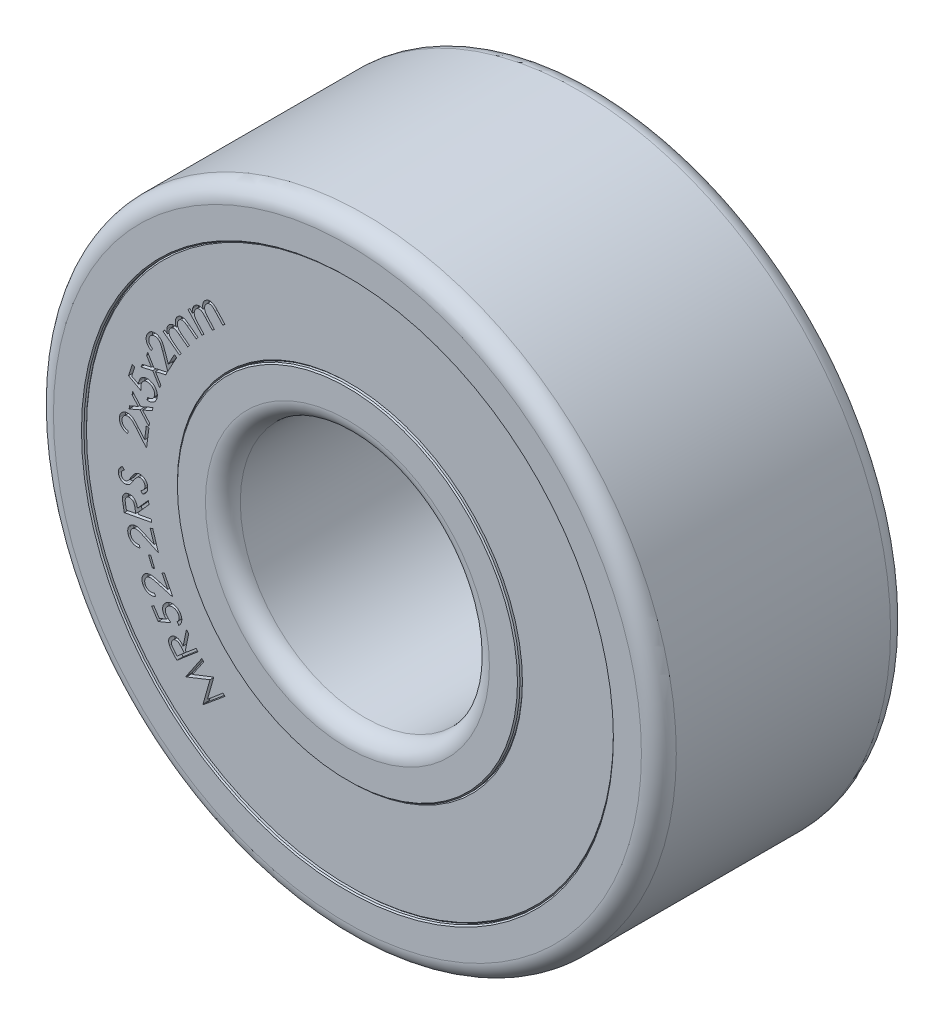
SolidWorks part; units mm, degrees
material "AISI 316 Annealed Stainless Steel Bar (SS)"
ref_plane "Front" through (0, 0, 0) normal (0, 0, 1) x (1, 0, 0)
ref_plane "Top" through (0, 0, 0) normal (0, 1, 0) x (1, 0, 0)
ref_plane "Right" through (0, 0, 0) normal (1, 0, 0) x (0, 0, -1)
sketch "LAYOUT R" plane through (0, 0, 0) normal (1, 0, 0) x (0, 0, -1)
  line L0 (-1, 1) -> (1, 1)
  line L1 (1, -2.5) -> (-1, -2.5) construction
  line L2 (1, -2.5) -> (1, 2.5) construction
  line L3 (1, 2.5) -> (-1, 2.5)
  line L4 (-1, -2.5) -> (-1, 2.5) construction
  line L5 (1, -2.5) -> (-1, 2.5) construction
  line L6 (1, 2.5) -> (-1, -2.5) construction
  line L7 (-1, 1.375) -> (1, 1.375)
  line L8 (-1, 2.125) -> (1, 2.125)
  line L11 (-17.5, 0) -> (17.5, 0) construction
  line L12 (-1, 2.5) -> (-1, 2.125)
  line L13 (1, 2.5) -> (1, 2.125)
  line L14 (-1, 2.125) -> (-1, 1.375)
  line L15 (1, 2.125) -> (1, 1.375)
  line L16 (-1, 1.375) -> (-1, 1)
  line L17 (1, 1.375) -> (1, 1)
  line L18 (-0.98, 2.125) -> (-0.98, 1.375)
  line L19 (0.98, 2.125) -> (0.98, 1.375)
  point P0 (0, 0)
  point P15 (0, 0)
  dimension "D1" = 2
  dimension "D2" = 5
  dimension "D3" = 1
  dimension "D6" = 0.02
  dimension "D7" = 0.02
  dimension "D4" = 1.375
  dimension "D5" = 2.125
sketch "Sketch R, INNER BODY" plane through (0, 0, 0) normal (1, 0, 0) x (0, 0, -1)
  line L0 (-1, 1) -> (1, 1) construction
  line L2 (-1, 1.375) -> (1, 1.375) construction
  line L4 (-1, 1) -> (1, 1)
  line L6 (-1, 1.375) -> (1, 1.375)
  line L8 (1, 1.375) -> (1, 1) construction
  line L9 (-1, 1.375) -> (-1, 1) construction
  line L10 (1, 1.375) -> (1, 1)
  line L11 (-1, 1.375) -> (-1, 1)
  line L12 (-17.5, 0) -> (17.5, 0) construction
  line L13 (-17.5, 0) -> (17.5, 0) construction
sketch "Sketch R, OUTER BODY" plane through (0, 0, 0) normal (1, 0, 0) x (0, 0, -1)
  line L2 (-1, 2.125) -> (1, 2.125) construction
  line L3 (1, 2.5) -> (-1, 2.5) construction
  line L6 (-1, 2.125) -> (1, 2.125)
  line L7 (1, 2.5) -> (-1, 2.5)
  line L8 (-17.5, 0) -> (17.5, 0) construction
  line L9 (-17.5, 0) -> (17.5, 0) construction
  line L10 (1, 2.5) -> (1, 2.125) construction
  line L11 (-1, 2.5) -> (-1, 2.125) construction
  line L12 (1, 2.5) -> (1, 2.125)
  line L13 (-1, 2.5) -> (-1, 2.125)
sketch "Sketch R, SEAL FACES" plane through (0, 0, 0) normal (1, 0, 0) x (0, 0, -1)
  line L0 (-17.5, 0) -> (17.5, 0) construction
  line L1 (-17.5, 0) -> (17.5, 0) construction
  line L3 (-1, 1.375) -> (1, 1.375) construction
  line L5 (-1, 2.125) -> (1, 2.125) construction
  line L7 (-0.98, 1.375) -> (0.98, 1.375)
  line L9 (-0.98, 2.125) -> (0.98, 2.125)
  line L10 (0.98, 2.125) -> (0.98, 1.375) construction
  line L11 (-0.98, 2.125) -> (-0.98, 1.375) construction
  line L12 (0.98, 2.125) -> (0.98, 1.375)
  line L13 (-0.98, 2.125) -> (-0.98, 1.375)
revolve "Revolve INNER BODY" add sketch "Sketch R, INNER BODY" angle 360 about L13
fillet "Fillet INNER BODY" radius 0.14 2 edges at (1, 0, 1) (1, 0, -1)
chamfer "Chamfer INNER BODY" distance 0.01 angle 45 2 edges at (1.375, 0, -1) (1.375, 0, 1)
revolve "Revolve OUTER BODY" add sketch "Sketch R, OUTER BODY" angle 360 about L9
fillet "Fillet OUTER BODY" radius 0.14 2 edges at (2.5, 0, -1) (2.5, 0, 1)
chamfer "Chamfer OUTER BODY" distance 0.01 angle 45 2 edges at (2.125, 0, 1) (2.125, 0, -1)
revolve "Revolve SEALS" add sketch "Sketch R, SEAL FACES" angle 360 about L1
chamfer "Chamfer SEALS" distance 0.01 angle 45 4 edges at (1.375, 0, -0.98) (2.125, 0, -0.98) (2.125, 0, 0.98) (1.375, 0, 0.98)
sketch "Sketch TEXT RADIUS 1 — MANUALLY ASSIGN TEXT AND FONT SIZE (FROM EQUATIONS)" plane through (0, 0, 0.98) normal (0, 0, 1) x (1, 0, 0)
  circle A0 centre (0, 0) radius 1.6375 construction
  text T0 "MR52-2RS  2x5x2mm" font "Century Gothic" height 0.225
  dimension "D1" = 3.275
extrude "Cut-Extrude SEAL LABEL 1" cut sketch "Sketch TEXT RADIUS 1 — MANUALLY ASSIGN TEXT AND FONT SIZE (FROM EQUATIONS)" against normal blind 0.05
sketch "Sketch TEXT RADIUS 2 — MANUALLY ASSIGN TEXT AND FONT SIZE (FROM EQUATIONS)" plane through (0, 0, -0.98) normal (0, 0, -1) x (-1, 0, 0)
  circle A0 centre (0, 0) radius 1.6375 construction
  text T0 "MR52-2RS  2x5x2mm" font "Century Gothic" height 0.225
  dimension "D1" = 3.275
extrude "Cut-Extrude SEAL LABEL 2" cut sketch "Sketch TEXT RADIUS 2 — MANUALLY ASSIGN TEXT AND FONT SIZE (FROM EQUATIONS)" against normal blind 0.05
equation "\"_i__BORE\"= 2"
equation "\"_i__OUTSIDE_DIAMETER\"= 5"
equation "\"_i__WIDTH\"= 2"
equation "\"_i_optional__TEXT_RADIUS_ADJUSTMENT\"= 0"
equation "\"_output__FONT_SIZE_mm\"= \"BODY_SPAN__SEAL__OF_RADIUS\" * \"param__FONT_SIZE_RATIO\"'MANUALLY ASSIGN TO FONT"
equation "\"BODY__HALF_WIDTH\"= \"_i__WIDTH\" / 2"
equation "\"BODY_SPAN___OF_DIAMETER\"= \"_i__OUTSIDE_DIAMETER\" - \"_i__BORE\""
equation "\"BODY_SPAN___OF_RADIUS\"= \"BODY_SPAN___OF_DIAMETER\" / 2"
equation "\"BODY_SPAN__BORE_AND_OD__OF RADIUS\"= ( \"BODY_SPAN___OF_RADIUS\" - \"BODY_SPAN__SEAL__OF_RADIUS\" ) / 2"
equation "\"BODY_SPAN__SEAL__OF_RADIUS\"= \"BODY_SPAN___OF_RADIUS\" * \"param__SEAL_PANEL_SPAN__RATIO_OF_BODY_RADIAN\""
equation "\"BORE__RADIUS\"= \"_i__BORE\" / 2"
equation "\"CORNER_RADII\"= \"_i__WIDTH\" * \"param__CORNER_RADII__ISO_MAX_RATIO_TO_WIDTH\""
equation "\"param__CORNER_RADII__ISO_MAX_RATIO_TO_WIDTH\"= 0.07'WHERE WIDTH IS LESS THAN DIAMETER"
equation "\"param__FONT_SIZE_RATIO\"= 0.3"
equation "\"param__SEAL_FACE_INSET__RATIO_OF_WIDTH\"= .01"
equation "\"param__SEAL_PANEL_SPAN__RATIO_OF_BODY_RADIAN\"= 0.5"
equation "\"param__SIDE_CHAMFERS__RATIO_TO_OD\"= 1 / 500"
equation "\"RING_INNER__OUTSIDE_RADIUS\"= \"BORE__RADIUS\" + \"BODY_SPAN__BORE_AND_OD__OF RADIUS\""
equation "\"RING_OUTER__OUTSIDE_RADIUS\"= ( \"_i__OUTSIDE_DIAMETER\" / 2 ) - \"BODY_SPAN__BORE_AND_OD__OF RADIUS\""
equation "\"SEAL_FACE_INSET\"= \"_i__WIDTH\" * \"param__SEAL_FACE_INSET__RATIO_OF_WIDTH\""
equation "\"SIDE_FACE_AND_SEAL_CHAMFERS\"= \"_i__OUTSIDE_DIAMETER\" * \"param__SIDE_CHAMFERS__RATIO_TO_OD\""
equation "\"TEXT_RADIUS\"= \"_i__BORE\" + ( \"BODY_SPAN___OF_DIAMETER\" / 2 ) - \"_output__FONT_SIZE_mm\" + \"_i_optional__TEXT_RADIUS_ADJUSTMENT\""
equation "\"D1@Chamfer INNER BODY\"=\"SIDE_FACE_AND_SEAL_CHAMFERS\""
equation "\"D1@Chamfer OUTER BODY\"=\"SIDE_FACE_AND_SEAL_CHAMFERS\""
equation "\"D1@Chamfer SEALS\"=\"SIDE_FACE_AND_SEAL_CHAMFERS\""
equation "\"D1@Fillet INNER BODY\"=\"CORNER_RADII\""
equation "\"D1@Fillet OUTER BODY\"=\"CORNER_RADII\""
equation "\"D1@LAYOUT R\"=\"_i__WIDTH\""
equation "\"D1@Sketch TEXT RADIUS 1 — MANUALLY ASSIGN TEXT AND FONT SIZE (FROM EQUATIONS)\" = \"TEXT_RADIUS\""
equation "\"D1@Sketch TEXT RADIUS 2 — MANUALLY ASSIGN TEXT AND FONT SIZE (FROM EQUATIONS)\" = \"TEXT_RADIUS\""
equation "\"D2@LAYOUT R\"=\"_i__OUTSIDE_DIAMETER\""
equation "\"D3@LAYOUT R\"=\"BORE__RADIUS\""
equation "\"D4@LAYOUT R\"=\"RING_INNER__OUTSIDE_RADIUS\""
equation "\"D5@LAYOUT R\"=\"RING_OUTER__OUTSIDE_RADIUS\""
